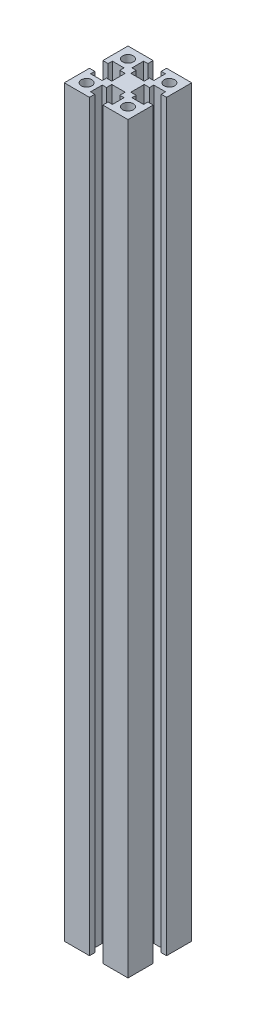
SolidWorks part; units mm, degrees
ref_plane "前视基准面" through (0, 0, 0) normal (0, 0, 1) x (1, 0, 0)
ref_plane "上视基准面" through (0, 0, 0) normal (0, 1, 0) x (1, 0, 0)
ref_plane "右视基准面" through (0, 0, 0) normal (1, 0, 0) x (0, 0, -1)
sketch "草图1" plane through (0, 0, 0) normal (0, 1, 0) x (1, 0, 0)
  line L0 (-15, -3.15) -> (-12.5, -3.15)
  line L1 (-15, 15) -> (-3.15, 15)
  line L2 (-15, 15) -> (-15, 3.15)
  line L3 (-15, -15) -> (-3.15, -15)
  line L4 (15, 15) -> (15, 3.15)
  line L5 (-15, 15) -> (15, -15) construction
  line L6 (-15, -15) -> (15, 15) construction
  line L7 (-12.5, -3.15) -> (-12.5, -5.15)
  line L8 (-12.5, -5.15) -> (-7, -5.15)
  line L9 (-7, -5.15) -> (-7, -3.15)
  line L10 (-7, -3.15) -> (-4.5, -3.15)
  line L11 (-4.5, -3.15) -> (-4.5, 3.15)
  line L12 (-4.5, 3.15) -> (-7, 3.15)
  line L13 (-7, 3.15) -> (-7, 5.15)
  line L14 (-7, 5.15) -> (-12.5, 5.15)
  line L15 (-12.5, 5.15) -> (-12.5, 3.15)
  line L16 (-12.5, 3.15) -> (-15, 3.15)
  line L17 (-15, 0) -> (-4.5, 0) construction
  line L18 (-15, -3.15) -> (-15, -15)
  line L19 (-15, 3.15) -> (-15, 0) construction
  line L20 (-15, 0) -> (-15, -3.15) construction
  line L21 (3.15, 12.5) -> (3.15, 15)
  line L22 (5.15, 12.5) -> (3.15, 12.5)
  line L23 (5.15, 7) -> (5.15, 12.5)
  line L24 (3.15, 7) -> (5.15, 7)
  line L25 (3.15, 4.5) -> (3.15, 7)
  line L26 (-3.15, 4.5) -> (3.15, 4.5)
  line L27 (-3.15, 7) -> (-3.15, 4.5)
  line L28 (-5.15, 7) -> (-3.15, 7)
  line L29 (-5.15, 12.5) -> (-5.15, 7)
  line L30 (-3.15, 12.5) -> (-5.15, 12.5)
  line L31 (-3.15, 15) -> (-3.15, 12.5)
  line L32 (12.5, -3.15) -> (15, -3.15)
  line L33 (12.5, -5.15) -> (12.5, -3.15)
  line L34 (7, -5.15) -> (12.5, -5.15)
  line L35 (7, -3.15) -> (7, -5.15)
  line L36 (4.5, -3.15) -> (7, -3.15)
  line L37 (4.5, 3.15) -> (4.5, -3.15)
  line L38 (7, 3.15) -> (4.5, 3.15)
  line L39 (7, 5.15) -> (7, 3.15)
  line L40 (12.5, 5.15) -> (7, 5.15)
  line L41 (12.5, 3.15) -> (12.5, 5.15)
  line L42 (15, 3.15) -> (12.5, 3.15)
  line L43 (-3.15, -12.5) -> (-3.15, -15)
  line L44 (-5.15, -12.5) -> (-3.15, -12.5)
  line L45 (-5.15, -7) -> (-5.15, -12.5)
  line L46 (-3.15, -7) -> (-5.15, -7)
  line L47 (-3.15, -4.5) -> (-3.15, -7)
  line L48 (3.15, -4.5) -> (-3.15, -4.5)
  line L49 (3.15, -7) -> (3.15, -4.5)
  line L50 (5.15, -7) -> (3.15, -7)
  line L51 (5.15, -12.5) -> (5.15, -7)
  line L52 (3.15, -12.5) -> (5.15, -12.5)
  line L53 (3.15, -15) -> (3.15, -12.5)
  line L54 (3.15, 15) -> (15, 15)
  line L55 (15, -3.15) -> (15, -15)
  line L56 (3.15, -15) -> (15, -15)
  line L57 (-5.15, -9.75) -> (-15, -9.75) construction
  line L58 (-9.75, -5.15) -> (-9.75, -15) construction
  circle A0 centre (-9.75, -9.75) radius 2.5
  circle A1 centre (-9.75, 9.75) radius 2.5
  circle A2 centre (9.75, 9.75) radius 2.5
  circle A3 centre (9.75, -9.75) radius 2.5
  point P0 (0, 0)
  point P59 (0, 0)
  point P72 (0, 0)
  dimension "D1" = 5
  dimension "D2" = 6.3
  dimension "D3" = 10.3
  dimension "D4" = 2.5
  dimension "D5" = 5.5
  dimension "D6" = 10.5
  dimension "D7" = 30
  dimension "D8" = 4
  dimension "D9" = 4
extrude "凸台-拉伸1" add sketch "草图1" along normal mid plane 360
sketch "草图2" plane through (0, 180, 0) normal (0, 1, 0) x (1, 0, 0)
  circle A0 centre (0, 0) radius 82.2505
extrude "切除-拉伸1" cut sketch "草图2" against normal blind 10
equation "\"零件重量\"= \"SW-质量\" / 1000"
